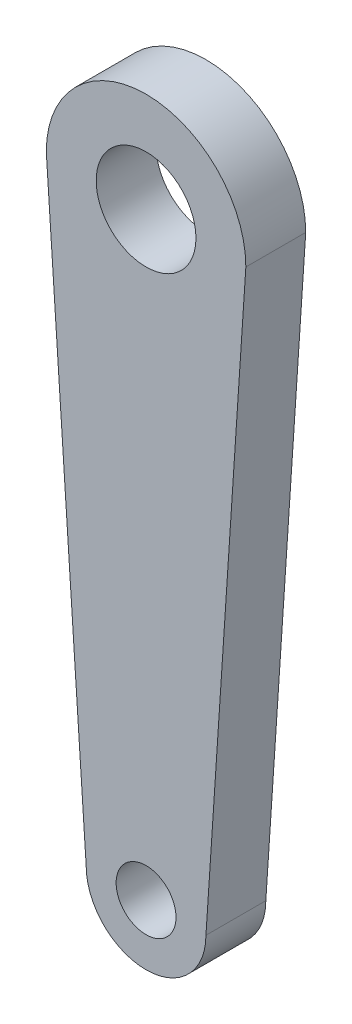
SolidWorks part; units mm, degrees
ref_plane "Front Plane" through (0, 0, 0) normal (0, 0, 1) x (1, 0, 0)
ref_plane "Top Plane" through (0, 0, 0) normal (0, 1, 0) x (1, 0, 0)
ref_plane "Right Plane" through (0, 0, 0) normal (1, 0, 0) x (0, 0, -1)
sketch "Sketch1" plane through (0, 0, 0) normal (0, 0, 1) x (1, 0, 0)
  line L0 (0, 0) -> (0, -30) construction
  line L1 (-5, 0) -> (-3, -30)
  line L2 (5, 0) -> (3, -30)
  arc A0 (5, 0) -> (-5, 0) centre (0, 0) ccw
  arc A1 (-3, -30) -> (3, -30) centre (0, -30) ccw
  dimension "D1" = 10
  dimension "D3" = 6
  dimension "D2" = 30
extrude "Boss-Extrude1" add sketch "Sketch1" along normal blind 3
sketch "Sketch2" plane through (0, 0, 3) normal (0, 0, 1) x (1, 0, 0)
  circle A0 centre (0, 0) radius 2.5
  dimension "D1" = 5
extrude "Cut-Extrude1" cut sketch "Sketch2" against normal through all
sketch "Sketch3" plane through (0, 0, 3) normal (0, 0, 1) x (1, 0, 0)
  line L0 (0, 0) -> (0, -33) construction
  arc A0 (-3, -30) -> (3, -30) centre (0, -30) ccw construction
  circle A1 centre (0, -29.9733) radius 1.5
  dimension "D1" = 3
extrude "Cut-Extrude2" cut sketch "Sketch3" against normal through all
